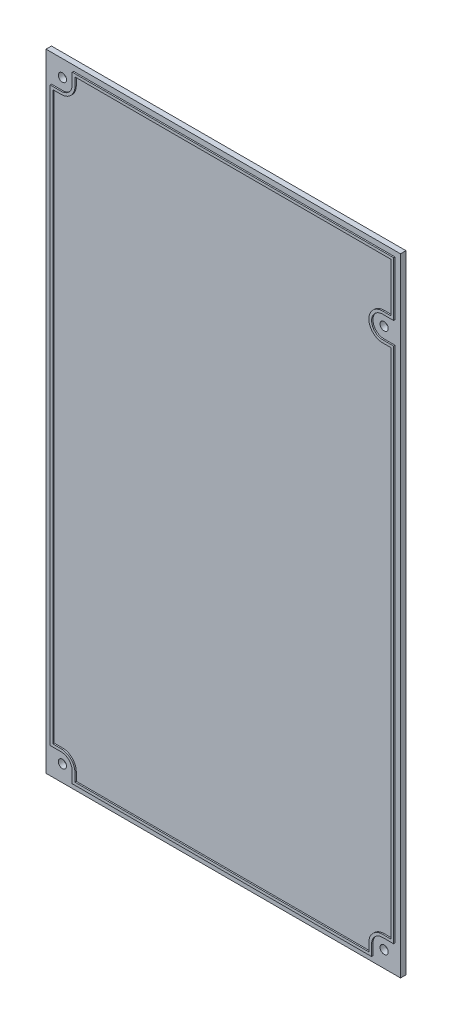
SolidWorks part; units mm, degrees
ref_plane "Front Plane" through (0, 0, 0) normal (0, 0, 1) x (1, 0, 0)
ref_plane "Top Plane" through (0, 0, 0) normal (0, 1, 0) x (1, 0, 0)
ref_plane "Right Plane" through (0, 0, 0) normal (1, 0, 0) x (0, 0, -1)
sketch "Sketch1" plane through (0, 0, 0) normal (0, 0, 1) x (1, 0, 0)
  line L1 (-65, -115) -> (65, -115)
  line L2 (-65, -115) -> (-65, 115)
  line L3 (-65, 115) -> (65, 115)
  line L4 (65, -115) -> (65, 115)
  line L5 (-65, -115) -> (65, 115) construction
  line L6 (-65, 115) -> (65, -115) construction
  point P0 (0, 0)
  dimension "D1" = 230
  dimension "D2" = 130
extrude "Boss-Extrude1" add sketch "Sketch1" along normal blind 2
sketch "Sketch2" plane through (0, 0, 2) normal (0, 0, 1) x (1, 0, 0)
  line L0 (65, -115) -> (65, 115) construction
  line L1 (-63, -113) -> (63, -113) construction
  line L2 (-63, -113) -> (-63, 113) construction
  line L3 (-63, 113) -> (63, 113) construction
  line L4 (63, -113) -> (63, 84.95) construction
  line L5 (-63, -113) -> (63, 113) construction
  line L6 (-63, 113) -> (63, -113) construction
  line L7 (65, 115) -> (-65, 115) construction
  line L8 (-63, -104.9) -> (-54.9, -113) construction
  line L9 (63, 93.05) -> (58.95, 93.05)
  line L11 (63, 84.95) -> (58.95, 84.95)
  line L13 (-63, 113) -> (-54.9, 113) construction
  line L14 (-63, 113) -> (-63, 104.9) construction
  line L15 (-63, 104.9) -> (-58.95, 104.9)
  line L16 (-54.9, 113) -> (-54.9, 108.95)
  line L17 (-63, -113) -> (-54.9, -113) construction
  line L18 (-63, -113) -> (-63, -104.9) construction
  line L19 (-63, -104.9) -> (-58.95, -104.9)
  line L20 (-54.9, -113) -> (-54.9, -108.95)
  line L21 (63, -113) -> (54.9, -113) construction
  line L22 (63, -113) -> (63, -104.9) construction
  line L23 (63, -104.9) -> (58.95, -104.9)
  line L24 (54.9, -113) -> (54.9, -108.95)
  line L25 (63, -104.9) -> (54.9, -113) construction
  line L26 (58.95, 93.05) -> (58.95, 84.95) construction
  line L27 (-54.9, 113) -> (-63, 104.9) construction
  line L28 (63, 84.95) -> (63, -104.9)
  line L29 (54.9, -113) -> (-54.9, -113)
  line L30 (-63, -104.9) -> (-63, 104.9)
  line L31 (-54.9, 113) -> (63, 113)
  line L32 (63, 113) -> (63, 93.05)
  line L33 (63, 93.05) -> (63, 113) construction
  circle A0 centre (-58.95, 108.95) radius 1.5 construction
  circle A1 centre (58.95, 89) radius 1.5 construction
  circle A2 centre (58.95, -108.95) radius 1.5 construction
  circle A3 centre (-58.95, -108.95) radius 1.5 construction
  arc A4 (-58.95, 104.9) -> (-54.9, 108.95) centre (-58.95, 108.95) ccw
  arc A5 (58.95, -104.9) -> (54.9, -108.95) centre (58.95, -108.95) ccw
  arc A6 (-58.95, -104.9) -> (-54.9, -108.95) centre (-58.95, -108.95) cw
  arc A7 (58.95, 93.05) -> (58.95, 84.95) centre (58.95, 89) ccw
  point P0 (0, 0)
  dimension "D12" = 3
  dimension "D13" = 4.05
  dimension "D1" = 2
  dimension "D2" = 2
  dimension "D3" = 8.1
  dimension "D4" = 8.1
  dimension "D5" = 8.1
  dimension "D6" = 4.05
  dimension "D7" = 8.1
  dimension "D8" = 8.1
  dimension "D9" = 8.1
  dimension "D10" = 8.1
  dimension "D11" = 19.95
extrude "Extrude-Thin1" add sketch "Sketch2" along normal blind 0.5 thin contours A7 L9 L32 L31 L16 A4 L15 L30 L19 A6 L20 L29 L24 A5 L23 L28 L11
sketch "Sketch3" plane through (0, 0, 2) normal (0, 0, 1) x (1, 0, 0)
  line L0 (58.95, 89) -> (59, 89) construction
  line L1 (58.95, 93.05) -> (58.95, 84.95) construction
  line L2 (63, 113) -> (63, 93.05) construction
  line L3 (-63, 113) -> (63, 113) construction
  line L5 (-63, -113) -> (-63, 113) construction
  line L6 (-63, -113) -> (63, -113) construction
  line L7 (63, -113) -> (63, 84.95) construction
  circle A0 centre (59, -109) radius 1.5
  circle A1 centre (-59, -109) radius 1.5
  circle A8 centre (-59, 109) radius 1.5
  circle A9 centre (59, 89) radius 1.5
  dimension "D1" = 3
  dimension "D2" = 4
  dimension "D3" = 4
  dimension "D4" = 4
  dimension "D5" = 4
  dimension "D6" = 4
  dimension "D7" = 4
  dimension "D8" = 4
extrude "Cut-Extrude1" cut sketch "Sketch3" against normal through all
